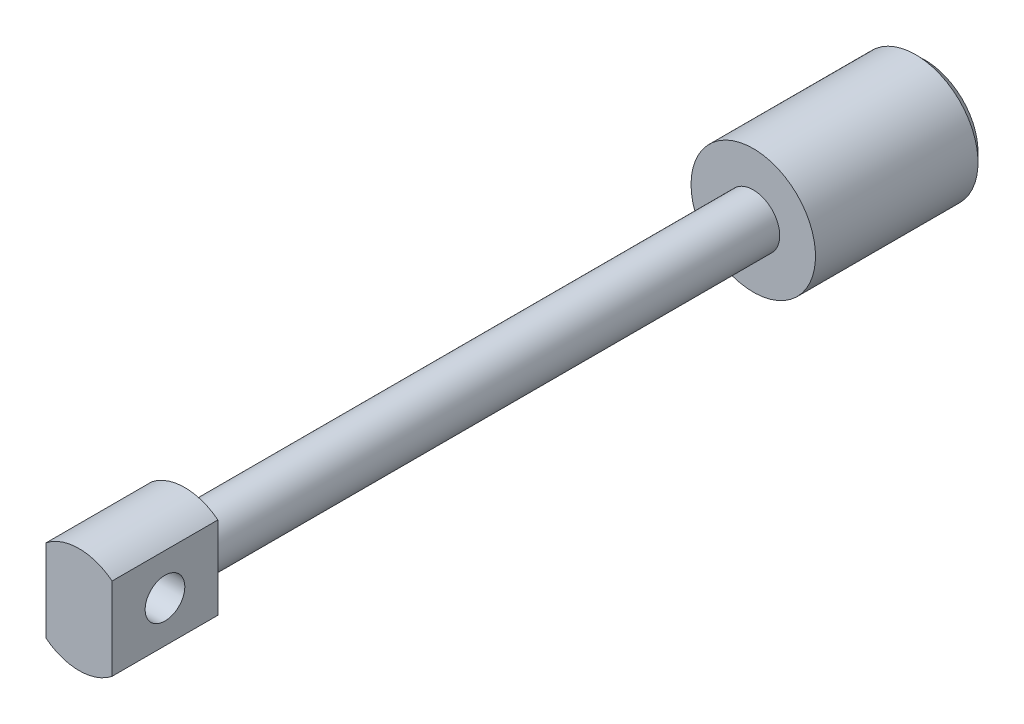
SolidWorks part; units mm, degrees
ref_plane "Plan de face" through (0, 0, 0) normal (0, 0, 1) x (1, 0, 0)
ref_plane "Plan de dessus" through (0, 0, 0) normal (0, 1, 0) x (1, 0, 0)
ref_plane "Plan de droite" through (0, 0, 0) normal (1, 0, 0) x (0, 0, -1)
sketch "Esquisse1" plane through (0, 0, 0) normal (0, 1, 0) x (1, 0, 0)
  line L0 (0, 0) -> (-8, 0)
  line L1 (-8, 0) -> (-8, 16)
  line L2 (-8, 16) -> (-4, 16)
  line L3 (-4, 16) -> (-4, 102)
  line L4 (-4, 102) -> (-9.4142, 102)
  line L5 (-9.4142, 102) -> (-9.4142, 126.5858)
  line L6 (-9.4142, 126.5858) -> (-8, 128)
  line L7 (-8, 128) -> (0, 128)
  line L8 (0, 128) -> (0, 0)
  dimension "D1" = 128
  dimension "D2" = 16
  dimension "D3" = 86
  dimension "D4" = 8
  dimension "D5" = 4
  dimension "D6" = 225
  dimension "D7" = 2
  dimension "D8" = 8
revolve "Révolution1" add sketch "Esquisse1" angle 360 about L8
sketch "Esquisse2" plane through (0, 0, 0) normal (0, 0, 1) x (1, 0, 0)
  line L0 (-5, 10) -> (-5, -12)
  line L1 (-5, -12) -> (5, -12)
  line L2 (5, -12) -> (5, 10)
  line L3 (5, 10) -> (12, 10)
  line L4 (12, 10) -> (12, -15)
  line L5 (12, -15) -> (-12, -15)
  line L6 (-12, -15) -> (-12, 10)
  line L7 (-12, 10) -> (-5, 10)
  dimension "D1" = 10
  dimension "D2" = 5
  dimension "D3" = 7
  dimension "D4" = 7
  dimension "D5" = 12
  dimension "D6" = 25
  dimension "D7" = 22
extrude "Enlèv. mat.-Extru.1" cut sketch "Esquisse2" against normal up to next
sketch "Esquisse3" plane through (-5, 0, 0) normal (-1, 0, 0) x (0, 0, 1)
  line L1 (0, 0) -> (-18.3357, 0) construction
  line L3 (-16, 4) -> (-16, -4) construction
  circle A0 centre (-8, 0) radius 3
  dimension "D2" = 6
  dimension "D1" = 8
extrude "Enlèv. mat.-Extru.2" cut sketch "Esquisse3" against normal up to next
